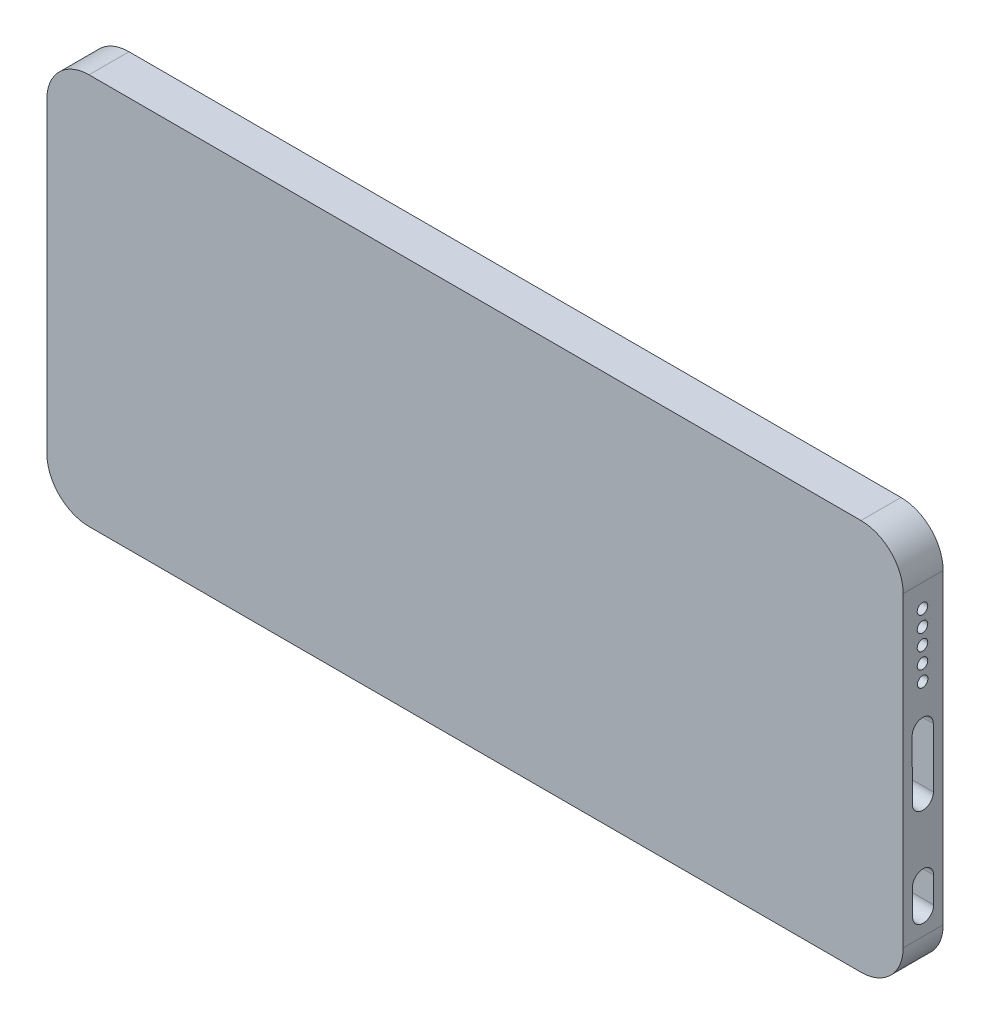
SolidWorks part; units mm, degrees
ref_plane "前视基准面" through (0, 0, 0) normal (0, 0, 1) x (1, 0, 0)
ref_plane "上视基准面" through (0, 0, 0) normal (0, 1, 0) x (1, 0, 0)
ref_plane "右视基准面" through (0, 0, 0) normal (1, 0, 0) x (0, 0, -1)
other "Configuration Table"
sketch "草图1" plane through (0, 0, 0) normal (0, 0, 1) x (1, 0, 0)
  line L1 (-77.3717, 43.4058) -> (69.0283, 43.4058)
  line L2 (-85.3717, 35.4058) -> (-85.3717, -22.7942)
  line L3 (-77.3717, -30.7942) -> (69.0283, -30.7942)
  line L4 (77.0283, 35.4058) -> (77.0283, -22.7942)
  arc A0 (-85.3717, 35.4058) -> (-77.3717, 43.4058) centre (-77.3717, 35.4058) cw
  arc A1 (69.0283, -30.7942) -> (77.0283, -22.7942) centre (69.0283, -22.7942) ccw
  arc A2 (77.0283, 35.4058) -> (69.0283, 43.4058) centre (69.0283, 35.4058) ccw
  arc A3 (-77.3717, -30.7942) -> (-85.3717, -22.7942) centre (-77.3717, -22.7942) cw
  point P6 (-85.3717, 43.4058)
  point P11 (77.0283, 43.4058)
  point P14 (-85.3717, -30.7942)
  dimension "D3" = 8
  dimension "D4" = 8
  dimension "D1" = 74.2
  dimension "D2" = 162.4
extrude "凸台-拉伸1" add sketch "草图1" along normal blind 7.58 contours L2 A3 L3 A1 L4 A2 L1 A0
sketch "草图2" plane through (77.0283, 0, 0) normal (1, 0, 0) x (0, 0, -1)
  line L0 (-3.9164, 18.0471) -> (-3.9164, 30.117) construction
  line L3 (-7.58, 35.4058) -> (0, 35.4058) construction
  line L4 (-7.58, -22.7942) -> (0, -22.7942) construction
  line L5 (-3.9265, 35.4058) -> (-3.79, -22.7942) construction
  line L6 (-3.8697, 11.1974) -> (-3.8433, -0.0523) construction
  line L7 (-1.8697, 11.2021) -> (-1.8433, -0.0476)
  line L8 (-5.8697, 11.1927) -> (-5.8433, -0.0569)
  line L9 (-3.8113, -13.6913) -> (-3.7998, -18.6282) construction
  line L10 (-1.8114, -13.6866) -> (-1.7998, -18.6235)
  line L11 (-5.8113, -13.696) -> (-5.7998, -18.6329)
  circle A2 centre (-3.9164, 31.0969) radius 1
  circle A3 centre (-3.9164, 28.0969) radius 1
  circle A4 centre (-3.9164, 25.0969) radius 1
  circle A5 centre (-3.9164, 22.0969) radius 1
  circle A6 centre (-3.8882, 19.0969) radius 1
  arc A7 (-1.8697, 11.2021) -> (-5.8697, 11.1927) centre (-3.8697, 11.1974) ccw
  arc A8 (-5.8433, -0.0569) -> (-1.8433, -0.0476) centre (-3.8433, -0.0523) ccw
  arc A9 (-1.8114, -13.6866) -> (-5.8113, -13.696) centre (-3.8113, -13.6913) ccw
  arc A10 (-5.7998, -18.6329) -> (-1.7998, -18.6235) centre (-3.7998, -18.6282) ccw
  point P2 (-3.9053, 24.2398)
  point P6 (-3.8565, 5.5726)
  point P28 (-3.8056, -16.1598)
  dimension "D1" = 3
  dimension "D5" = 11.2496
  dimension "D7" = 2
  dimension "D2" = 3
  dimension "D3" = 3
  dimension "D4" = 3
  dimension "D6" = 58.2002
extrude "切除-拉伸1" cut sketch "草图2" against normal blind 10 contours L8 A8 L7 A7 | A6 | A5 | A4 | A2 | A3 | L11 A9 L10 A10
